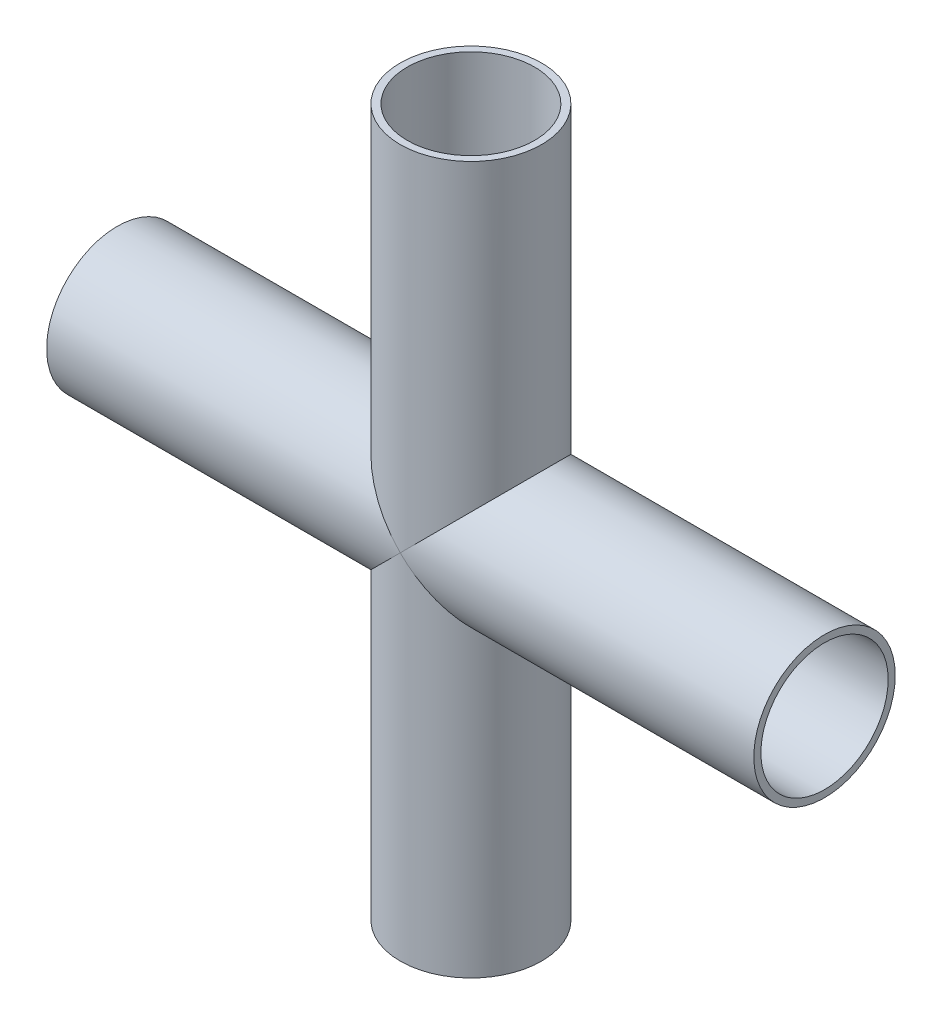
SolidWorks part; units mm, degrees
ref_plane "Front Plane" through (0, 0, 0) normal (0, 0, 1) x (1, 0, 0)
ref_plane "Top Plane" through (0, 0, 0) normal (0, 1, 0) x (1, 0, 0)
ref_plane "Right Plane" through (0, 0, 0) normal (1, 0, 0) x (0, 0, -1)
sketch "Sketch1" plane through (0, 0, 0) normal (0, 1, 0) x (1, 0, 0)
  circle A0 centre (0, 0) radius 1
  circle A1 centre (0, 0) radius 0.9
  dimension "D1" = 2
  dimension "D2" = 1.8
extrude "Boss-Extrude1" add sketch "Sketch1" along normal blind 10
sketch "Sketch2" plane through (0, 0, 0) normal (1, 0, 0) x (0, 0, -1)
  line L0 (0, 10) -> (0, 0) construction
  line L1 (1, 10) -> (-1, 10) construction
  line L2 (-1, 0) -> (1, 0) construction
  circle A0 centre (0, 5) radius 0.9
  circle A1 centre (0, 5) radius 1
  dimension "D1" = 2
  dimension "D2" = 1.8
extrude "Boss-Extrude2" add sketch "Sketch2" along normal mid plane 10
sketch "Sketch4" plane through (0, 0, 0) normal (0, -1, 0) x (1, 0, 0)
  circle A0 centre (0, 0) radius 0.9 construction
  circle A1 centre (0, 0) radius 0.9
extrude "Cut-Extrude2" cut sketch "Sketch4" against normal through all
sketch "Sketch5" plane through (5, 0, 0) normal (1, 0, 0) x (0, 0, -1)
  circle A0 centre (0, 5) radius 0.9 construction
  circle A1 centre (0, 5) radius 0.9
extrude "Cut-Extrude3" cut sketch "Sketch5" against normal through all
